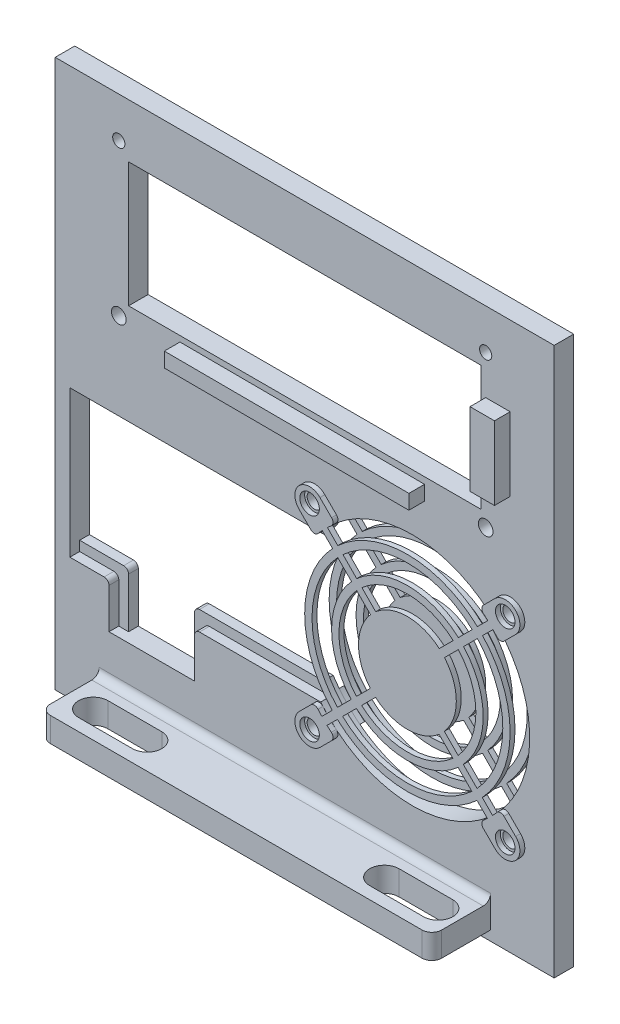
SolidWorks part; units mm, degrees
ref_plane "Front Plane" through (0, 0, 0) normal (0, 0, 1) x (1, 0, 0)
ref_plane "Top Plane" through (0, 0, 0) normal (0, 1, 0) x (1, 0, 0)
ref_plane "Right Plane" through (0, 0, 0) normal (1, 0, 0) x (0, 0, -1)
sketch "Sketch1" plane through (0, 0, 0) normal (0, 0, 1) x (1, 0, 0)
  line L1 (0, 0) -> (100, 0)
  line L2 (0, 0) -> (0, 112)
  line L3 (0, 112) -> (100, 112)
  line L4 (100, 0) -> (100, 112)
  dimension "D1" = 100
  dimension "D2" = 112
extrude "Boss-Extrude1" add sketch "Sketch1" along normal blind 4
sketch "Sketch2" plane through (0, 0, 4) normal (0, 0, 1) x (1, 0, 0)
  line L0 (0, 0) -> (100, 0) construction
  line L1 (8, 7) -> (88, 7)
  line L2 (8, 7) -> (8, 2)
  line L3 (8, 2) -> (88, 2)
  line L4 (88, 7) -> (88, 2)
  line L5 (0, 112) -> (0, 0) construction
  line L6 (100, 0) -> (100, 112) construction
  dimension "D1" = 2
  dimension "D2" = 5
  dimension "D3" = 8
  dimension "D4" = 12
extrude "Boss-Extrude2" add sketch "Sketch2" along normal blind 12
sketch "Sketch4" plane through (0, 7, 0) normal (0, 1, 0) x (1, 0, 0)
  line L0 (83.792, -10.5) -> (72.792, -10.5) construction
  line L3 (88, -4) -> (8, -4) construction
  line L5 (83.792, -13.5) -> (72.792, -13.5)
  line L6 (83.792, -7.5) -> (72.792, -7.5)
  line L7 (78.292, -12) -> (78.292, -9.1487) construction
  line L12 (73.584, -12) -> (83, -12) construction
  line L13 (18.292, -12) -> (18.292, -9.1487) construction
  line L14 (24.292, -10.5) -> (13.292, -10.5) construction
  line L15 (24.292, -13.5) -> (13.292, -13.5)
  line L16 (24.292, -7.5) -> (13.292, -7.5)
  arc A2 (83.792, -13.5) -> (83.792, -7.5) centre (83.792, -10.5) ccw
  arc A3 (72.792, -7.5) -> (72.792, -13.5) centre (72.792, -10.5) ccw
  arc A4 (24.292, -13.5) -> (24.292, -7.5) centre (24.292, -10.5) ccw
  arc A5 (13.292, -7.5) -> (13.292, -13.5) centre (13.292, -10.5) ccw
  point P6 (78.292, -10.5)
  point P11 (78.292, -7.5)
  point P16 (18.792, -10.5)
  dimension "D3" = 6.5
  dimension "D1" = 3
  dimension "D2" = 11
  dimension "D4" = 6.5
extrude "Cut-Extrude1" cut sketch "Sketch4" against normal blind 10 contours A3 L5 A2 L6 | A5 L15 A4 L16
fillet "Fillet1" radius 2 2 edges at (88, 4.5, 16) (8, 4.5, 16)
sketch "Sketch5" plane through (0, 0, 4) normal (0, 0, 1) x (1, 0, 0)
  line L0 (100, 112) -> (0, 112) construction
  line L1 (47, 40) -> (17.6449, 40) construction
  line L2 (50, 112) -> (50, 90) construction
  line L3 (0, 0) -> (100, 0) construction
  line L4 (12, 103.75) -> (12, 72.75) construction
  line L5 (2, 53) -> (47, 53)
  line L6 (2, 53) -> (2, 27)
  line L7 (2, 27) -> (47, 27)
  line L8 (47, 53) -> (47, 27) construction
  line L9 (14, 101) -> (86, 101)
  line L10 (14, 101) -> (14, 75.5)
  line L11 (14, 75.5) -> (86, 75.5)
  line L12 (86, 101) -> (86, 75.5)
  line L14 (0, 112) -> (0, 0) construction
  line L15 (47, 53) -> (51.8258, 53)
  line L16 (47, 27) -> (51.8258, 27)
  line L18 (52, 60) -> (92, 20) construction
  circle A0 centre (12, 103.75) radius 1.25
  circle A1 centre (87, 103.75) radius 1.25
  arc A2 (51.8258, 27) -> (51.8258, 53) centre (72, 40) ccw
  circle A3 centre (12, 72.75) radius 1.25
  circle A4 centre (87, 72.75) radius 1.25
  circle A5 centre (92, 60) radius 1.5
  circle A6 centre (52, 60) radius 1.5
  circle A7 centre (52, 20) radius 1.5
  circle A8 centre (92, 20) radius 1.5
  point P16 (24.5, 53)
  point P23 (14, 88.25)
  point P24 (12, 88.25)
  point P25 (50, 101)
  point P41 (72, 40)
  point P44 (72, 40)
  dimension "D1" = 2.5
  dimension "D2" = 48
  dimension "D3" = 40
  dimension "D8" = 75
  dimension "D9" = 31
  dimension "D12" = 2
  dimension "D14" = 3
  dimension "D15" = 40
  dimension "D16" = 40
  dimension "D4" = 26
  dimension "D5" = 45
  dimension "D6" = 72
  dimension "D7" = 25.5
  dimension "D10" = 2
  dimension "D11" = 11
  dimension "D13" = 25
extrude "Cut-Extrude2" cut sketch "Sketch5" against normal blind 10
fillet "Fillet2" radius 1.5 1 edges at (48, 7, 4)
sketch "Sketch6" plane through (0, 0, 4) normal (0, 0, 1) x (1, 0, 0)
  line L1 (51.8258, 53) -> (2, 53)
  line L3 (52, 55) -> (2, 55)
  line L4 (2, 53) -> (2, 55)
  line L5 (51.8258, 27) -> (2, 27)
  line L7 (51.8258, 25) -> (2, 25)
  line L8 (2, 27) -> (2, 25)
  line L9 (52, 55) -> (58.675, 55)
  line L11 (51.8258, 53) -> (58.675, 53)
  line L12 (58.675, 55) -> (58.675, 53)
  line L13 (51.8258, 25) -> (57.3197, 25)
  line L15 (51.8258, 27) -> (57.3197, 27)
  line L16 (57.3197, 25) -> (57.3197, 27)
  line L17 (2, 53) -> (2, 27) construction
  dimension "D1" = 2
  dimension "D2" = 50
extrude "Cut-Extrude3" cut sketch "Sketch6" against normal blind 2
sketch "Sketch8" plane through (0, 0, 0) normal (-1, 0, 0) x (0, 0, 1)
  line L6 (0, 112) -> (0, 0)
  line L7 (0, 0) -> (4, 0)
  line L8 (4, 0) -> (4, 112)
  line L9 (4, 112) -> (0, 112)
  line L10 (0, 112) -> (0, 0)
  line L11 (0, 0) -> (4, 0)
  line L12 (4, 0) -> (4, 112)
  line L13 (4, 112) -> (0, 112)
  dimension "D1" = 0
extrude "Boss-Extrude3" add sketch "Sketch8" along normal blind 1
sketch "Sketch9" plane through (100, 0, 0) normal (1, 0, 0) x (0, 0, -1)
  line L4 (0, 0) -> (0, 112)
  line L5 (0, 112) -> (-4, 112)
  line L6 (-4, 112) -> (-4, 0)
  line L7 (-4, 0) -> (0, 0)
  line L8 (0, 0) -> (0, 112)
  line L9 (0, 112) -> (-4, 112)
  line L10 (-4, 112) -> (-4, 0)
  line L11 (-4, 0) -> (0, 0)
  dimension "D1" = 0
extrude "Boss-Extrude4" add sketch "Sketch9" along normal blind 1
sketch "Sketch10" plane through (0, 0, 4) normal (0, 0, 1) x (1, 0, 0)
  line L0 (87, 72.75) -> (87, 103.75) construction
  line L2 (87, 80.75) -> (92, 80.75)
  line L3 (87, 80.75) -> (87, 95.75)
  line L4 (87, 95.75) -> (92, 95.75)
  line L5 (92, 80.75) -> (92, 95.75)
  point P8 (87, 88.25)
  point P9 (87, 88.25)
  dimension "D1" = 15
  dimension "D2" = 5
extrude "Boss-Extrude5" add sketch "Sketch10" along normal blind 3.2
sketch "Sketch11" plane through (0, 0, 4) normal (0, 0, 1) x (1, 0, 0)
  line L1 (12, 27) -> (25.5, 27)
  line L2 (12, 27) -> (12, 15.8)
  line L3 (12, 15.8) -> (25.5, 15.8)
  line L4 (25.5, 27) -> (25.5, 15.8)
  line L5 (2, 55) -> (2, 25) construction
  line L6 (51.8258, 27) -> (2, 27) construction
  dimension "D1" = 13.5
  dimension "D2" = 10
  dimension "D3" = 11.2
extrude "Cut-Extrude4" cut sketch "Sketch11" against normal blind 10 contours L2 L3 L4 L1
sketch "Sketch12" plane through (0, 0, 4) normal (0, 0, 1) x (1, 0, 0)
  line L0 (10, 25) -> (10, 15.8)
  line L1 (2, 25) -> (12, 25) construction
  line L2 (12, 25) -> (12, 15.8) construction
  line L3 (10, 25) -> (12, 25)
  line L4 (12, 25) -> (12, 15.8)
  line L5 (12, 15.8) -> (10, 15.8)
  line L6 (18.75, 15.8) -> (18.75, 21.7118) construction
  line L7 (12, 15.8) -> (25.5, 15.8) construction
  line L8 (25.5, 15.8) -> (27.5, 15.8)
  line L9 (25.5, 25) -> (25.5, 15.8)
  line L10 (27.5, 25) -> (25.5, 25)
  line L11 (27.5, 25) -> (27.5, 15.8)
  dimension "D1" = 2
extrude "Cut-Extrude5" cut sketch "Sketch12" against normal blind 2
fillet "Fillet3" radius 1 4 edges at (25.5, 27, 1) (12, 27, 1) (27.5, 25, 3) (10, 25, 3)
sketch "Sketch13" plane through (0, 0, 4) normal (0, 0, 1) x (1, 0, 0)
  circle A0 centre (12, 72.75) radius 1.5
  circle A1 centre (87, 72.75) radius 1.5
  dimension "D1" = 3
extrude "Cut-Extrude6" cut sketch "Sketch13" against normal through all
sketch "Sketch15" plane through (0, 0, 4) normal (0, 0, 1) x (1, 0, 0)
  line L0 (12, 72.75) -> (87, 72.75) construction
  line L1 (74.5055, 74.1559) -> (24.5058, 74.344)
  line L2 (74.5055, 74.1559) -> (74.4942, 71.156)
  line L3 (24.5058, 74.344) -> (24.4945, 71.3441)
  line L4 (74.4942, 71.156) -> (24.4945, 71.3441)
  line L5 (74.5055, 74.1559) -> (24.4945, 71.3441) construction
  line L6 (24.5058, 74.344) -> (74.4942, 71.156) construction
  point P4 (49.5, 72.75)
  point P5 (49.5, 72.75)
  dimension "D1" = 50
  dimension "D2" = 3
extrude "Boss-Extrude6" add sketch "Sketch15" along normal blind 3.2
sketch "Sketch16" plane through (0, 0, 0) normal (0, 0, -1) x (-1, 0, 0)
  line L0 (-94.1213, 57.8787) -> (-90.9588, 54.7161)
  line L1 (-89.8787, 62.1213) -> (-86.7161, 58.9588)
  line L2 (-54.1213, 62.1213) -> (-57.2839, 58.9588)
  line L3 (-89.8787, 17.8787) -> (-86.7161, 21.0412)
  line L4 (-54.5887, 56.518) -> (-56.7007, 54.3851)
  line L8 (-55.6545, 57.5734) -> (-57.7665, 55.4405)
  line L13 (-54.5074, 23.5681) -> (-56.6299, 25.6906)
  line L14 (-55.5681, 22.5074) -> (-57.6906, 24.6299)
  line L15 (-69.9454, 42.188) -> (-69.8329, 42.0755)
  line L16 (-53.0412, 25.2839) -> (-49.8787, 22.1213)
  line L17 (-53.0412, 54.7161) -> (-49.8787, 57.8787)
  line L18 (-86.3094, 55.3701) -> (-88.4319, 57.4926)
  line L19 (-87.3701, 54.3094) -> (-89.4926, 56.4319)
  line L20 (-57.2839, 21.0412) -> (-54.1213, 17.8787)
  line L21 (-72.5136, 39.453) -> (-72.5418, 39.4811)
  line L22 (-71.4582, 40.5189) -> (-71.4864, 40.547)
  line L23 (-78.5208, 47.5815) -> (-81.3549, 50.4156)
  line L24 (-79.5815, 46.5208) -> (-82.4156, 49.3549)
  line L25 (-74.1671, 37.9245) -> (-74.0546, 37.812)
  line L26 (-78.4833, 32.3864) -> (-81.3035, 29.5384)
  line L27 (-79.5492, 33.4419) -> (-82.3693, 30.5938)
  line L28 (-90.9588, 25.2839) -> (-94.1213, 22.1213)
  line L29 (-58.8227, 54.3739) -> (-65.5167, 47.6136)
  line L30 (-57.7568, 53.3185) -> (-64.4508, 46.5581)
  line L31 (-82.417, 51.4776) -> (-85.248, 54.3087)
  line L32 (-83.4776, 50.417) -> (-86.3087, 53.248)
  line L33 (-62.6451, 29.5844) -> (-65.4792, 32.4185)
  line L34 (-61.5844, 30.6451) -> (-64.4185, 33.4792)
  line L35 (-58.752, 25.6913) -> (-61.583, 28.5224)
  line L36 (-57.6913, 26.752) -> (-60.5224, 29.583)
  line L37 (-82.3602, 28.4711) -> (-85.1773, 25.6261)
  line L38 (-83.4261, 29.5265) -> (-86.2432, 26.6815)
  line L39 (-86.2335, 24.5595) -> (-88.3455, 22.4266)
  line L40 (-87.2993, 25.6149) -> (-89.4113, 23.482)
  arc A0 (-79.5815, 46.5208) -> (-79.5492, 33.4419) centre (-72, 40) ccw
  circle A1 centre (-92, 60) radius 2
  circle A2 centre (-52, 60) radius 2
  circle A3 centre (-52, 20) radius 2
  circle A4 centre (-92, 20) radius 2
  arc A5 (-89.8787, 62.1213) -> (-94.1213, 57.8787) centre (-92, 60) ccw
  arc A6 (-94.1213, 22.1213) -> (-89.8787, 17.8787) centre (-92, 20) ccw
  arc A7 (-49.8787, 57.8787) -> (-54.1213, 62.1213) centre (-52, 60) ccw
  arc A8 (-54.1213, 17.8787) -> (-49.8787, 22.1213) centre (-52, 20) ccw
  arc A9 (-82.4156, 49.3549) -> (-82.3693, 30.5938) centre (-72, 40) ccw
  arc A10 (-83.4776, 50.417) -> (-83.4261, 29.5265) centre (-72, 40) ccw
  arc A11 (-86.3087, 53.248) -> (-86.2432, 26.6815) centre (-72, 40) ccw
  arc A12 (-87.3701, 54.3094) -> (-87.2993, 25.6149) centre (-72, 40) ccw
  arc A13 (-51.8258, 53) -> (-51.8258, 27) centre (-72, 40) ccw construction
  circle A14 centre (-92, 60) radius 3 construction
  circle A15 centre (-52, 60) radius 3 construction
  circle A16 centre (-52, 20) radius 3 construction
  circle A17 centre (-92, 20) radius 3 construction
  arc A18 (-53.0412, 54.7161) -> (-54.5887, 56.518) centre (-72, 40) ccw
  arc A19 (-90.9588, 25.2839) -> (-89.4113, 23.482) centre (-72, 40) ccw
  arc A20 (-57.2839, 21.0412) -> (-55.5681, 22.5074) centre (-72, 40) ccw
  arc A21 (-86.7161, 58.9588) -> (-88.4319, 57.4926) centre (-72, 40) ccw
  arc A22 (-89.4926, 56.4319) -> (-90.9588, 54.7161) centre (-72, 40) ccw
  arc A23 (-88.3455, 22.4266) -> (-86.7161, 21.0412) centre (-72, 40) ccw
  arc A24 (-65.5167, 47.6136) -> (-78.5208, 47.5815) centre (-72, 40) ccw
  circle A25 centre (-72, 40) radius 21 construction
  circle A26 centre (-72, 40) radius 15.5 construction
  circle A27 centre (-72, 40) radius 19.5 construction
  circle A28 centre (-72, 40) radius 14 construction
  circle A29 centre (-72, 40) radius 10 construction
  arc A30 (-78.4833, 32.3864) -> (-64.4508, 46.5581) centre (-72, 40) ccw
  arc A31 (-81.3035, 29.5384) -> (-62.6451, 29.5844) centre (-72, 40) ccw
  arc A32 (-82.3602, 28.4711) -> (-61.583, 28.5224) centre (-72, 40) ccw
  arc A33 (-85.1773, 25.6261) -> (-58.752, 25.6913) centre (-72, 40) ccw
  arc A34 (-86.2335, 24.5595) -> (-57.6906, 24.6299) centre (-72, 40) ccw
  arc A35 (-54.5074, 23.5681) -> (-53.0412, 25.2839) centre (-72, 40) ccw
  arc A36 (-57.6913, 26.752) -> (-57.7568, 53.3185) centre (-72, 40) ccw
  arc A37 (-56.6299, 25.6906) -> (-56.7007, 54.3851) centre (-72, 40) ccw
  arc A38 (-61.5844, 30.6451) -> (-61.6307, 49.4062) centre (-72, 40) ccw
  arc A39 (-60.5224, 29.583) -> (-60.5739, 50.4735) centre (-72, 40) ccw
  arc A40 (-55.6545, 57.5734) -> (-57.2839, 58.9588) centre (-72, 40) ccw
  arc A41 (-57.7665, 55.4405) -> (-86.3094, 55.3701) centre (-72, 40) ccw
  arc A42 (-58.8227, 54.3739) -> (-85.248, 54.3087) centre (-72, 40) ccw
  arc A43 (-61.6398, 51.5289) -> (-82.417, 51.4776) centre (-72, 40) ccw
  arc A44 (-62.6965, 50.4616) -> (-81.3549, 50.4156) centre (-72, 40) ccw
  point P16 (-49, 60)
  point P20 (-49, 20)
  point P22 (-89, 20)
  point P32 (-62.437, 42.9237)
  point P34 (-52.5, 40)
  point P36 (-58, 40)
  point P38 (-56.5, 40)
  point P39 (-89, 60)
  point P106 (-51, 40)
  dimension "D1" = 20
  dimension "D2" = 4
  dimension "D3" = 1
  dimension "D4" = 1
  dimension "D5" = 1
  dimension "D6" = 1
  dimension "D7" = 4
  dimension "D8" = 1.5
  dimension "D9" = 4
  dimension "D10" = 1.5
extrude "Boss-Extrude7" add sketch "Sketch16" along normal blind 1 separate body
pattern_linear "LPattern2" count 2 spacing 5 along (0, 0, 1) of "Boss-Extrude7"
fillet "Fillet4" radius 1 8 edges at (57.2839, 58.9588, 4.5) (53.0412, 54.7161, 4.5) (53.0412, 25.2839, 4.5) (57.2839, 21.0412, 4.5) (86.7161, 21.0412, 4.5) (90.9588, 25.2839, 4.5) (90.9588, 54.7161, 4.5) (86.7161, 58.9588, 4.5)
